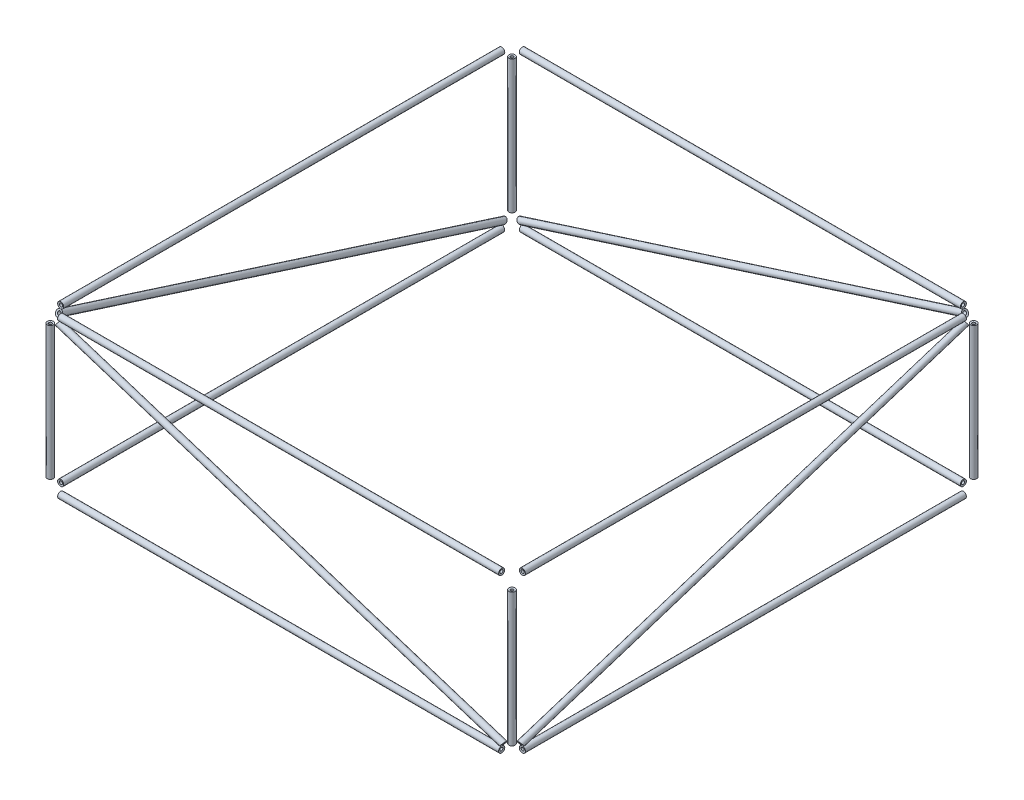
SolidWorks part; units mm, degrees
material "Hexcel AS4C (3000 Filaments)"
ref_plane "前基準面" through (0, 0, 0) normal (0, 0, 1) x (1, 0, 0)
ref_plane "上基準面" through (0, 0, 0) normal (0, 1, 0) x (1, 0, 0)
ref_plane "右基準面" through (0, 0, 0) normal (1, 0, 0) x (0, 0, -1)
sketch3d "3D草圖1"
  line L0 (-150, 0, -150) -> (-150, 0, 150)
  line L1 (-150, 0, 150) -> (150, 0, 150)
  line L3 (150, 0, 150) -> (150, 0, -150)
  line L4 (150, 0, -150) -> (-150, 0, -150)
  line L6 (150, 0, -150) -> (150, 100, -150)
  line L7 (150, 0, -150) -> (-150, 0, 150) construction
  line L8 (150, 0, 150) -> (-150, 0, -150) construction
  line L21 (150, 100, -150) -> (-150, 100, -150)
  line L22 (-150, 100, -150) -> (-150, 100, 150)
  line L23 (-150, 100, 150) -> (150, 100, 150)
  line L24 (150, 100, 150) -> (150, 100, -150)
  line L25 (150, 100, 150) -> (150, 0, 150)
  line L26 (-150, 0, 150) -> (-150, 100, 150)
  line L27 (-150, 0, -150) -> (-150, 100, -150)
  line L28 (150, 98, -150) -> (150, 2, 150)
  line L29 (150, 2, 150) -> (-150, 98, 150)
  line L30 (-150, 98, 150) -> (-150, 2, -150)
  line L31 (-150, 2, -150) -> (150, 98, -150)
  dimension "D1" = 300
  dimension "D3" = 100
  dimension "D2" = 100
  dimension "D4" = 2
  dimension "D5" = 2
  dimension "D6" = 17.745
other "管路 4 X 1(1)"
ref_plane "平面1" through (150, 100, -150) normal (-1, 0, 0) x (0, 0, 1)
sketch "Sketch1" plane through (150, 100, -150) normal (-1, 0, 0) x (0, 0, 1)
  circle A0 centre (0, 0) radius 1
  circle A1 centre (0, 0) radius 2
  point P3 (0, 0)
  dimension "In_dia" = 2
  dimension "Out_dia" = 4
sketch "草圖4" plane through (0, 0, 0) normal (0, 1, 0) x (1, 0, 0)
  line L0 (150, -150) -> (150, 150) construction
  line L1 (150, -143) -> (150, -157)
  arc A2 (150, -143) -> (150, -157) centre (150, -150) cw
  point P6 (0, 0)
  dimension "D1" = 7
revolve "除料-旋轉6" cut sketch "草圖4" angle 360 about L1
sketch "草圖5" plane through (0, 0, 0) normal (0, 1, 0) x (1, 0, 0)
  line L0 (150, 150) -> (-150, 150) construction
  line L1 (143, 150) -> (157, 150)
  arc A0 (143, 150) -> (157, 150) centre (150, 150) ccw
  dimension "D1" = 7
revolve "除料-旋轉7" cut sketch "草圖5" angle 360 about L1
ref_plane "平面2" through (0, 100, 0) normal (0, -1, 0) x (-1, 0, 0)
sketch "草圖6" plane through (0, 100, 0) normal (0, -1, 0) x (-1, 0, 0)
  line L0 (-150, 150) -> (150, 150) construction
  line L1 (-143, 150) -> (-157, 150)
  arc A0 (-143, 150) -> (-157, 150) centre (-150, 150) cw
  dimension "D1" = 7
revolve "除料-旋轉8" cut sketch "草圖6" angle 360 about L1
sketch "草圖7" plane through (0, 100, 0) normal (0, -1, 0) x (-1, 0, 0)
  line L0 (150, -150) -> (-150, -150) construction
  line L1 (-143, -150) -> (-157, -150)
  arc A0 (-143, -150) -> (-157, -150) centre (-150, -150) ccw
  dimension "D1" = 7
revolve "除料-旋轉9" cut sketch "草圖7" angle 360 about L1
sketch "草圖8" plane through (0, 0, 0) normal (0, 1, 0) x (1, 0, 0)
  line L0 (-150, 150) -> (-150, -150) construction
  line L1 (-150, -157) -> (-150, -143)
  arc A0 (-150, -143) -> (-150, -157) centre (-150, -150) cw
  dimension "D1" = 7
revolve "除料-旋轉10" cut sketch "草圖8" angle 360 about L1
sketch "草圖9" plane through (0, 0, 0) normal (0, 1, 0) x (1, 0, 0)
  line L0 (150, 150) -> (-150, 150) construction
  line L1 (-143, 150) -> (-157, 150)
  arc A0 (-143, 150) -> (-157, 150) centre (-150, 150) ccw
  dimension "D1" = 7
revolve "除料-旋轉11" cut sketch "草圖9" angle 360 about L1
sketch "草圖10" plane through (0, 100, 0) normal (0, -1, 0) x (-1, 0, 0)
  line L0 (150, -150) -> (-150, -150) construction
  line L1 (143, -150) -> (157, -150)
  arc A0 (143, -150) -> (157, -150) centre (150, -150) ccw
  dimension "D1" = 7
revolve "除料-旋轉12" cut sketch "草圖10" angle 360 about L1
sketch "草圖11" plane through (0, 100, 0) normal (0, -1, 0) x (-1, 0, 0)
  line L0 (-150, 150) -> (150, 150) construction
  line L1 (143, 150) -> (157, 150)
  arc A0 (143, 150) -> (157, 150) centre (150, 150) ccw
  dimension "D1" = 7
revolve "除料-旋轉13" cut sketch "草圖11" angle 360 about L1
